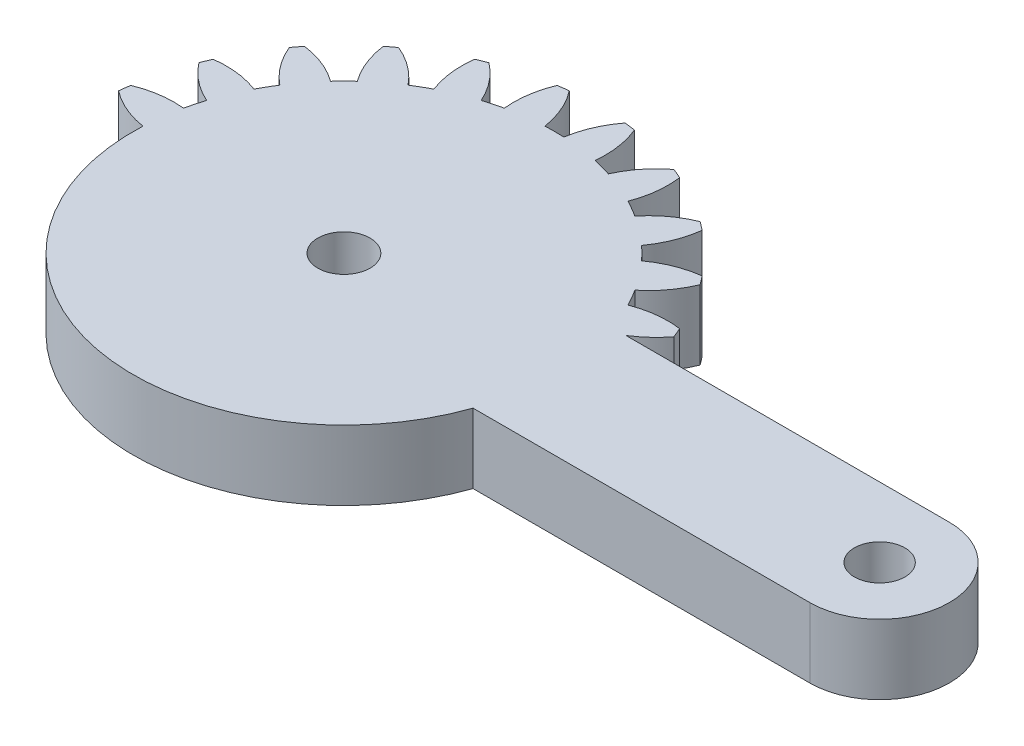
SolidWorks part; units mm, degrees
ref_plane "Front Plane" through (0, 0, 0) normal (0, 0, 1) x (1, 0, 0)
ref_plane "Top Plane" through (0, 0, 0) normal (0, 1, 0) x (1, 0, 0)
ref_plane "Right Plane" through (0, 0, 0) normal (1, 0, 0) x (0, 0, -1)
sketch "Sketch1" plane through (0, 0, 0) normal (0, 1, 0) x (1, 0, 0)
  line L0 (20.6437, 4) -> (2.0816, 4)
  line L1 (2.0816, -4) -> (20.6437, -4)
  arc A0 (2.0816, 4) -> (3.5217, 5.3071) centre (-0.7683, 8.5867) ccw
  arc A1 (3.5217, 5.3071) -> (3.2829, 5.8838) centre (-10.1063, 0) ccw
  arc A2 (3.2829, 5.8838) -> (0.6271, 5.5703) centre (2.5684, 0.5313) ccw
  arc A3 (0.6271, 5.5703) -> (0.0844, 6.5103) centre (-10.1063, 0) ccw
  arc A4 (0.0844, 6.5103) -> (1.6838, 8.6535) centre (-3.3089, 10.711) ccw
  arc A5 (1.6838, 8.6535) -> (1.3038, 9.1487) centre (-10.1063, 0) ccw
  arc A6 (1.3038, 9.1487) -> (-1.1803, 8.1585) centre (1.999, 3.7936) ccw
  arc A7 (-1.1803, 8.1585) -> (-1.9479, 8.926) centre (-10.1063, 0) ccw
  arc A8 (-1.9479, 8.926) -> (-0.9576, 11.4102) centre (-6.3127, 12.1053) ccw
  arc A9 (-0.9576, 11.4102) -> (-1.4528, 11.7901) centre (-10.1063, 0) ccw
  arc A10 (-1.4528, 11.7901) -> (-3.596, 10.1907) centre (0.6046, 6.7975) ccw
  arc A11 (-3.596, 10.1907) -> (-4.5361, 10.7334) centre (-10.1063, 0) ccw
  arc A12 (-4.5361, 10.7334) -> (-4.2225, 13.3892) centre (-9.5751, 12.6747) ccw
  arc A13 (-4.2225, 13.3892) -> (-4.7992, 13.6281) centre (-10.1063, 0) ccw
  arc A14 (-4.7992, 13.6281) -> (-6.4554, 11.5285) centre (-1.5196, 9.3381) ccw
  arc A15 (-6.4554, 11.5285) -> (-7.5039, 11.8094) centre (-10.1063, 0) ccw
  arc A16 (-7.5039, 11.8094) -> (-7.8884, 14.4558) centre (-12.8736, 12.3803) ccw
  arc A17 (-7.8884, 14.4558) -> (-8.5072, 14.5373) centre (-10.1063, 0) ccw
  arc A18 (-8.5072, 14.5373) -> (-9.5636, 12.0806) centre (-4.2291, 11.2423) ccw
  arc A19 (-9.5636, 12.0806) -> (-10.6491, 12.0806) centre (-10.1063, 0) ccw
  arc A20 (-10.6491, 12.0806) -> (-11.7054, 14.5373) centre (-15.9836, 11.2423) ccw
  arc A21 (-11.7054, 14.5373) -> (-12.3243, 14.4558) centre (-10.1063, 0) ccw
  arc A22 (-12.3243, 14.4558) -> (-12.7088, 11.8094) centre (-7.3391, 12.3803) ccw
  arc A23 (-12.7088, 11.8094) -> (-13.7573, 11.5285) centre (-10.1063, 0) ccw
  arc A24 (-13.7573, 11.5285) -> (-15.4135, 13.6281) centre (-18.6931, 9.3381) ccw
  arc A25 (-15.4135, 13.6281) -> (-15.9901, 13.3892) centre (-10.1063, 0) ccw
  arc A26 (-15.9901, 13.3892) -> (-15.6766, 10.7334) centre (-10.6376, 12.6747) ccw
  arc A27 (-15.6766, 10.7334) -> (-16.6166, 10.1907) centre (-10.1063, 0) ccw
  arc A28 (-16.6166, 10.1907) -> (-18.7599, 11.7901) centre (-20.8173, 6.7975) ccw
  arc A29 (-18.7599, 11.7901) -> (-19.255, 11.4102) centre (-10.1063, 0) ccw
  arc A30 (-19.255, 11.4102) -> (-18.2648, 8.926) centre (-13.9, 12.1053) ccw
  arc A31 (-18.2648, 8.926) -> (-19.0324, 8.1585) centre (-10.1063, 0) ccw
  arc A32 (-19.0324, 8.1585) -> (-21.5165, 9.1487) centre (-22.2117, 3.7936) ccw
  arc A33 (-21.5165, 9.1487) -> (-21.8965, 8.6535) centre (-10.1063, 0) ccw
  arc A34 (-21.8965, 8.6535) -> (-20.2971, 6.5103) centre (-16.9038, 10.711) ccw
  arc A35 (-20.2971, 6.5103) -> (-20.8398, 5.5703) centre (-10.1063, 0) ccw
  arc A36 (-20.8398, 5.5703) -> (-23.4956, 5.8838) centre (-22.7811, 0.5313) ccw
  arc A37 (-23.4956, 5.8838) -> (-23.7344, 5.3071) centre (-10.1063, 0) ccw
  arc A38 (-23.7344, 5.3071) -> (-21.6348, 3.6509) centre (-19.4444, 8.5867) ccw
  arc A39 (-21.6348, 3.6509) -> (-21.9157, 2.6025) centre (-10.1063, 0) ccw
  arc A40 (-21.9157, 2.6025) -> (-24.5622, 2.2179) centre (-22.4867, -2.7673) ccw
  arc A41 (-24.5622, 2.2179) -> (-24.6437, 1.5991) centre (-10.1063, 0) ccw
  arc A42 (-24.6437, 1.5991) -> (-22.1869, 0.5427) centre (-21.3486, 5.8773) ccw
  arc A43 (-22.1869, 0.5427) -> (-22.1869, -0.5427) centre (-10.1063, 0) ccw
  arc A44 (-22.1869, -0.5427) -> (-24.6437, -1.5991) centre (-21.3486, -5.8773) ccw
  arc A45 (-24.6437, -1.5991) -> (-24.5622, -2.2179) centre (-10.1063, 0) ccw
  arc A46 (-24.5622, -2.2179) -> (-21.9157, -2.6025) centre (-22.4867, 2.7673) ccw
  arc A47 (-21.9157, -2.6025) -> (-21.6348, -3.6509) centre (-10.1063, 0) ccw
  arc A48 (-21.6348, -3.6509) -> (-23.7344, -5.3071) centre (-19.4444, -8.5867) ccw
  arc A49 (-23.7344, -5.3071) -> (-23.4956, -5.8838) centre (-10.1063, 0) ccw
  arc A50 (-23.4956, -5.8838) -> (-20.8398, -5.5703) centre (-22.7811, -0.5313) ccw
  arc A51 (-20.8398, -5.5703) -> (-20.2971, -6.5103) centre (-10.1063, 0) ccw
  arc A52 (-20.2971, -6.5103) -> (-21.8965, -8.6535) centre (-16.9038, -10.711) ccw
  arc A53 (-21.8965, -8.6535) -> (-21.5165, -9.1487) centre (-10.1063, 0) ccw
  arc A54 (-21.5165, -9.1487) -> (-19.0324, -8.1585) centre (-22.2117, -3.7936) ccw
  arc A55 (-19.0324, -8.1585) -> (-18.2648, -8.926) centre (-10.1063, 0) ccw
  arc A56 (-18.2648, -8.926) -> (-19.255, -11.4102) centre (-13.9, -12.1053) ccw
  arc A57 (-19.255, -11.4102) -> (-18.7599, -11.7901) centre (-10.1063, 0) ccw
  arc A58 (-18.7599, -11.7901) -> (-16.6166, -10.1907) centre (-20.8173, -6.7975) ccw
  arc A59 (-16.6166, -10.1907) -> (-15.6766, -10.7334) centre (-10.1063, 0) ccw
  arc A60 (-15.6766, -10.7334) -> (-15.9901, -13.3892) centre (-10.6376, -12.6747) ccw
  arc A61 (-15.9901, -13.3892) -> (-15.4135, -13.6281) centre (-10.1063, 0) ccw
  arc A62 (-15.4135, -13.6281) -> (-13.7573, -11.5285) centre (-18.6931, -9.3381) ccw
  arc A63 (-13.7573, -11.5285) -> (-12.7088, -11.8094) centre (-10.1063, 0) ccw
  arc A64 (-12.7088, -11.8094) -> (-12.3243, -14.4558) centre (-7.3391, -12.3803) ccw
  arc A65 (-12.3243, -14.4558) -> (-11.7054, -14.5373) centre (-10.1063, 0) ccw
  arc A66 (-11.7054, -14.5373) -> (-10.6491, -12.0806) centre (-15.9836, -11.2423) ccw
  arc A67 (-10.6491, -12.0806) -> (-9.5636, -12.0806) centre (-10.1063, 0) ccw
  arc A68 (-9.5636, -12.0806) -> (-8.5072, -14.5373) centre (-4.2291, -11.2423) ccw
  arc A69 (-8.5072, -14.5373) -> (-7.8884, -14.4558) centre (-10.1063, 0) ccw
  arc A70 (-7.8884, -14.4558) -> (-7.5039, -11.8094) centre (-12.8736, -12.3803) ccw
  arc A71 (-7.5039, -11.8094) -> (-6.4554, -11.5285) centre (-10.1063, 0) ccw
  arc A72 (-6.4554, -11.5285) -> (-4.7992, -13.6281) centre (-1.5196, -9.3381) ccw
  arc A73 (-4.7992, -13.6281) -> (-4.2225, -13.3892) centre (-10.1063, 0) ccw
  arc A74 (-4.2225, -13.3892) -> (-4.5361, -10.7334) centre (-9.5751, -12.6747) ccw
  arc A75 (-4.5361, -10.7334) -> (-3.596, -10.1907) centre (-10.1063, 0) ccw
  arc A76 (-3.596, -10.1907) -> (-1.4528, -11.7901) centre (0.6046, -6.7975) ccw
  arc A77 (-1.4528, -11.7901) -> (-0.9576, -11.4102) centre (-10.1063, 0) ccw
  arc A78 (-0.9576, -11.4102) -> (-1.9479, -8.926) centre (-6.3127, -12.1053) ccw
  arc A79 (-1.9479, -8.926) -> (-1.1803, -8.1585) centre (-10.1063, 0) ccw
  arc A80 (-1.1803, -8.1585) -> (1.3038, -9.1487) centre (1.999, -3.7936) ccw
  arc A81 (1.3038, -9.1487) -> (1.6838, -8.6535) centre (-10.1063, 0) ccw
  arc A82 (1.6838, -8.6535) -> (0.0844, -6.5103) centre (-3.3089, -10.711) ccw
  arc A83 (0.0844, -6.5103) -> (0.6271, -5.5703) centre (-10.1063, 0) ccw
  arc A84 (0.6271, -5.5703) -> (3.2829, -5.8838) centre (2.5684, -0.5313) ccw
  arc A85 (3.2829, -5.8838) -> (3.5217, -5.3071) centre (-10.1063, 0) ccw
  arc A86 (3.5217, -5.3071) -> (2.0816, -4) centre (-0.7683, -8.5867) ccw
  arc A87 (20.6437, -4) -> (20.6437, 4) centre (20.6437, 0) ccw
  circle A88 centre (-10.1063, 0) radius 1.5
  circle A89 centre (20.6437, 0) radius 1.45
  dimension "D1" = 3
  dimension "D2" = 2.9
extrude "Boss-Extrude1" add sketch "Sketch1" along normal blind 4
sketch "Sketch2" plane through (0, 4, 0) normal (0, 1, 0) x (1, 0, 0)
  line L0 (2.0816, -4) -> (1.3057, -4)
  line L2 (20.6437, 4) -> (2.0816, 4)
  line L3 (2.0816, -4) -> (20.6437, -4)
  line L4 (20.6437, 4) -> (2.0816, 4)
  line L5 (2.0816, -4) -> (20.6437, -4)
  circle A0 centre (-10.1063, 0) radius 12.0927
  arc A88 (20.6437, -4) -> (20.6437, 4) centre (20.6437, 0) ccw
  arc A89 (2.0816, 4) -> (3.5217, 5.3071) centre (-0.7683, 8.5867) ccw
  arc A90 (3.5217, 5.3071) -> (3.2829, 5.8838) centre (-10.1063, 0) ccw
  arc A91 (3.2829, 5.8838) -> (0.6271, 5.5703) centre (2.5684, 0.5313) ccw
  arc A92 (0.6271, 5.5703) -> (0.0844, 6.5103) centre (-10.1063, 0) ccw
  arc A93 (0.0844, 6.5103) -> (1.6838, 8.6535) centre (-3.3089, 10.711) ccw
  arc A94 (1.6838, 8.6535) -> (1.3038, 9.1487) centre (-10.1063, 0) ccw
  arc A95 (1.3038, 9.1487) -> (-1.1803, 8.1585) centre (1.999, 3.7936) ccw
  arc A96 (-1.1803, 8.1585) -> (-1.9479, 8.926) centre (-10.1063, 0) ccw
  arc A97 (-1.9479, 8.926) -> (-0.9576, 11.4102) centre (-6.3127, 12.1053) ccw
  arc A98 (-0.9576, 11.4102) -> (-1.4528, 11.7901) centre (-10.1063, 0) ccw
  arc A99 (-1.4528, 11.7901) -> (-3.596, 10.1907) centre (0.6046, 6.7975) ccw
  arc A100 (-3.596, 10.1907) -> (-4.5361, 10.7334) centre (-10.1063, 0) ccw
  arc A101 (-4.5361, 10.7334) -> (-4.2225, 13.3892) centre (-9.5751, 12.6747) ccw
  arc A102 (-4.2225, 13.3892) -> (-4.7992, 13.6281) centre (-10.1063, 0) ccw
  arc A103 (-4.7992, 13.6281) -> (-6.4554, 11.5285) centre (-1.5196, 9.3381) ccw
  arc A104 (-6.4554, 11.5285) -> (-7.5039, 11.8094) centre (-10.1063, 0) ccw
  arc A105 (-7.5039, 11.8094) -> (-7.8884, 14.4558) centre (-12.8736, 12.3803) ccw
  arc A106 (-7.8884, 14.4558) -> (-8.5072, 14.5373) centre (-10.1063, 0) ccw
  arc A107 (-8.5072, 14.5373) -> (-9.5636, 12.0806) centre (-4.2291, 11.2423) ccw
  arc A108 (-9.5636, 12.0806) -> (-10.6491, 12.0806) centre (-10.1063, 0) ccw
  arc A109 (-10.6491, 12.0806) -> (-11.7054, 14.5373) centre (-15.9836, 11.2423) ccw
  arc A110 (-11.7054, 14.5373) -> (-12.3243, 14.4558) centre (-10.1063, 0) ccw
  arc A111 (-12.3243, 14.4558) -> (-12.7088, 11.8094) centre (-7.3391, 12.3803) ccw
  arc A112 (-12.7088, 11.8094) -> (-13.7573, 11.5285) centre (-10.1063, 0) ccw
  arc A113 (-13.7573, 11.5285) -> (-15.4135, 13.6281) centre (-18.6931, 9.3381) ccw
  arc A114 (-15.4135, 13.6281) -> (-15.9901, 13.3892) centre (-10.1063, 0) ccw
  arc A115 (-15.9901, 13.3892) -> (-15.6766, 10.7334) centre (-10.6376, 12.6747) ccw
  arc A116 (-15.6766, 10.7334) -> (-16.6166, 10.1907) centre (-10.1063, 0) ccw
  arc A117 (-16.6166, 10.1907) -> (-18.7599, 11.7901) centre (-20.8173, 6.7975) ccw
  arc A118 (-18.7599, 11.7901) -> (-19.255, 11.4102) centre (-10.1063, 0) ccw
  arc A119 (-19.255, 11.4102) -> (-18.2648, 8.926) centre (-13.9, 12.1053) ccw
  arc A120 (-18.2648, 8.926) -> (-19.0324, 8.1585) centre (-10.1063, 0) ccw
  arc A121 (-19.0324, 8.1585) -> (-21.5165, 9.1487) centre (-22.2117, 3.7936) ccw
  arc A122 (-21.5165, 9.1487) -> (-21.8965, 8.6535) centre (-10.1063, 0) ccw
  arc A123 (-21.8965, 8.6535) -> (-20.2971, 6.5103) centre (-16.9038, 10.711) ccw
  arc A124 (-20.2971, 6.5103) -> (-20.8398, 5.5703) centre (-10.1063, 0) ccw
  arc A125 (-20.8398, 5.5703) -> (-23.4956, 5.8838) centre (-22.7811, 0.5313) ccw
  arc A126 (-23.4956, 5.8838) -> (-23.7344, 5.3071) centre (-10.1063, 0) ccw
  arc A127 (-23.7344, 5.3071) -> (-21.6348, 3.6509) centre (-19.4444, 8.5867) ccw
  arc A128 (-21.6348, 3.6509) -> (-21.9157, 2.6025) centre (-10.1063, 0) ccw
  arc A129 (-21.9157, 2.6025) -> (-24.5622, 2.2179) centre (-22.4867, -2.7673) ccw
  arc A130 (-24.5622, 2.2179) -> (-24.6437, 1.5991) centre (-10.1063, 0) ccw
  arc A131 (-24.6437, 1.5991) -> (-22.1869, 0.5427) centre (-21.3486, 5.8773) ccw
  arc A132 (-22.1869, 0.5427) -> (-22.1869, -0.5427) centre (-10.1063, 0) ccw
  arc A133 (-22.1869, -0.5427) -> (-24.6437, -1.5991) centre (-21.3486, -5.8773) ccw
  arc A134 (-24.6437, -1.5991) -> (-24.5622, -2.2179) centre (-10.1063, 0) ccw
  arc A135 (-24.5622, -2.2179) -> (-21.9157, -2.6025) centre (-22.4867, 2.7673) ccw
  arc A136 (-21.9157, -2.6025) -> (-21.6348, -3.6509) centre (-10.1063, 0) ccw
  arc A137 (-21.6348, -3.6509) -> (-23.7344, -5.3071) centre (-19.4444, -8.5867) ccw
  arc A138 (-23.7344, -5.3071) -> (-23.4956, -5.8838) centre (-10.1063, 0) ccw
  arc A139 (-23.4956, -5.8838) -> (-20.8398, -5.5703) centre (-22.7811, -0.5313) ccw
  arc A140 (-20.8398, -5.5703) -> (-20.2971, -6.5103) centre (-10.1063, 0) ccw
  arc A141 (-20.2971, -6.5103) -> (-21.8965, -8.6535) centre (-16.9038, -10.711) ccw
  arc A142 (-21.8965, -8.6535) -> (-21.5165, -9.1487) centre (-10.1063, 0) ccw
  arc A143 (-21.5165, -9.1487) -> (-19.0324, -8.1585) centre (-22.2117, -3.7936) ccw
  arc A144 (-19.0324, -8.1585) -> (-18.2648, -8.926) centre (-10.1063, 0) ccw
  arc A145 (-18.2648, -8.926) -> (-19.255, -11.4102) centre (-13.9, -12.1053) ccw
  arc A146 (-19.255, -11.4102) -> (-18.7599, -11.7901) centre (-10.1063, 0) ccw
  arc A147 (-18.7599, -11.7901) -> (-16.6166, -10.1907) centre (-20.8173, -6.7975) ccw
  arc A148 (-16.6166, -10.1907) -> (-15.6766, -10.7334) centre (-10.1063, 0) ccw
  arc A149 (-15.6766, -10.7334) -> (-15.9901, -13.3892) centre (-10.6376, -12.6747) ccw
  arc A150 (-15.9901, -13.3892) -> (-15.4135, -13.6281) centre (-10.1063, 0) ccw
  arc A151 (-15.4135, -13.6281) -> (-13.7573, -11.5285) centre (-18.6931, -9.3381) ccw
  arc A152 (-13.7573, -11.5285) -> (-12.7088, -11.8094) centre (-10.1063, 0) ccw
  arc A153 (-12.7088, -11.8094) -> (-12.3243, -14.4558) centre (-7.3391, -12.3803) ccw
  arc A154 (-12.3243, -14.4558) -> (-11.7054, -14.5373) centre (-10.1063, 0) ccw
  arc A155 (-11.7054, -14.5373) -> (-10.6491, -12.0806) centre (-15.9836, -11.2423) ccw
  arc A156 (-10.6491, -12.0806) -> (-9.5636, -12.0806) centre (-10.1063, 0) ccw
  arc A157 (-9.5636, -12.0806) -> (-8.5072, -14.5373) centre (-4.2291, -11.2423) ccw
  arc A158 (-8.5072, -14.5373) -> (-7.8884, -14.4558) centre (-10.1063, 0) ccw
  arc A159 (-7.8884, -14.4558) -> (-7.5039, -11.8094) centre (-12.8736, -12.3803) ccw
  arc A160 (-7.5039, -11.8094) -> (-6.4554, -11.5285) centre (-10.1063, 0) ccw
  arc A161 (-6.4554, -11.5285) -> (-4.7992, -13.6281) centre (-1.5196, -9.3381) ccw
  arc A162 (-4.7992, -13.6281) -> (-4.2225, -13.3892) centre (-10.1063, 0) ccw
  arc A163 (-4.2225, -13.3892) -> (-4.5361, -10.7334) centre (-9.5751, -12.6747) ccw
  arc A164 (-4.5361, -10.7334) -> (-3.596, -10.1907) centre (-10.1063, 0) ccw
  arc A165 (-3.596, -10.1907) -> (-1.4528, -11.7901) centre (0.6046, -6.7975) ccw
  arc A166 (-1.4528, -11.7901) -> (-0.9576, -11.4102) centre (-10.1063, 0) ccw
  arc A167 (-0.9576, -11.4102) -> (-1.9479, -8.926) centre (-6.3127, -12.1053) ccw
  arc A168 (-1.9479, -8.926) -> (-1.1803, -8.1585) centre (-10.1063, 0) ccw
  arc A169 (-1.1803, -8.1585) -> (1.3038, -9.1487) centre (1.999, -3.7936) ccw
  arc A170 (1.3038, -9.1487) -> (1.6838, -8.6535) centre (-10.1063, 0) ccw
  arc A171 (1.6838, -8.6535) -> (0.0844, -6.5103) centre (-3.3089, -10.711) ccw
  arc A172 (0.0844, -6.5103) -> (0.6271, -5.5703) centre (-10.1063, 0) ccw
  arc A173 (0.6271, -5.5703) -> (3.2829, -5.8838) centre (2.5684, -0.5313) ccw
  arc A174 (3.2829, -5.8838) -> (3.5217, -5.3071) centre (-10.1063, 0) ccw
  arc A175 (3.5217, -5.3071) -> (2.0816, -4) centre (-0.7683, -8.5867) ccw
  arc A176 (20.6437, -4) -> (20.6437, 4) centre (20.6437, 0) ccw
  arc A177 (2.0816, 4) -> (3.5217, 5.3071) centre (-0.7683, 8.5867) ccw
  arc A178 (3.5217, 5.3071) -> (3.2829, 5.8838) centre (-10.1063, 0) ccw
  arc A179 (3.2829, 5.8838) -> (0.6271, 5.5703) centre (2.5684, 0.5313) ccw
  arc A180 (0.6271, 5.5703) -> (0.0844, 6.5103) centre (-10.1063, 0) ccw
  arc A181 (0.0844, 6.5103) -> (1.6838, 8.6535) centre (-3.3089, 10.711) ccw
  arc A182 (1.6838, 8.6535) -> (1.3038, 9.1487) centre (-10.1063, 0) ccw
  arc A183 (1.3038, 9.1487) -> (-1.1803, 8.1585) centre (1.999, 3.7936) ccw
  arc A184 (-1.1803, 8.1585) -> (-1.9479, 8.926) centre (-10.1063, 0) ccw
  arc A185 (-1.9479, 8.926) -> (-0.9576, 11.4102) centre (-6.3127, 12.1053) ccw
  arc A186 (-0.9576, 11.4102) -> (-1.4528, 11.7901) centre (-10.1063, 0) ccw
  arc A187 (-1.4528, 11.7901) -> (-3.596, 10.1907) centre (0.6046, 6.7975) ccw
  arc A188 (-3.596, 10.1907) -> (-4.5361, 10.7334) centre (-10.1063, 0) ccw
  arc A189 (-4.5361, 10.7334) -> (-4.2225, 13.3892) centre (-9.5751, 12.6747) ccw
  arc A190 (-4.2225, 13.3892) -> (-4.7992, 13.6281) centre (-10.1063, 0) ccw
  arc A191 (-4.7992, 13.6281) -> (-6.4554, 11.5285) centre (-1.5196, 9.3381) ccw
  arc A192 (-6.4554, 11.5285) -> (-7.5039, 11.8094) centre (-10.1063, 0) ccw
  arc A193 (-7.5039, 11.8094) -> (-7.8884, 14.4558) centre (-12.8736, 12.3803) ccw
  arc A194 (-7.8884, 14.4558) -> (-8.5072, 14.5373) centre (-10.1063, 0) ccw
  arc A195 (-8.5072, 14.5373) -> (-9.5636, 12.0806) centre (-4.2291, 11.2423) ccw
  arc A196 (-9.5636, 12.0806) -> (-10.6491, 12.0806) centre (-10.1063, 0) ccw
  arc A197 (-10.6491, 12.0806) -> (-11.7054, 14.5373) centre (-15.9836, 11.2423) ccw
  arc A198 (-11.7054, 14.5373) -> (-12.3243, 14.4558) centre (-10.1063, 0) ccw
  arc A199 (-12.3243, 14.4558) -> (-12.7088, 11.8094) centre (-7.3391, 12.3803) ccw
  arc A200 (-12.7088, 11.8094) -> (-13.7573, 11.5285) centre (-10.1063, 0) ccw
  arc A201 (-13.7573, 11.5285) -> (-15.4135, 13.6281) centre (-18.6931, 9.3381) ccw
  arc A202 (-15.4135, 13.6281) -> (-15.9901, 13.3892) centre (-10.1063, 0) ccw
  arc A203 (-15.9901, 13.3892) -> (-15.6766, 10.7334) centre (-10.6376, 12.6747) ccw
  arc A204 (-15.6766, 10.7334) -> (-16.6166, 10.1907) centre (-10.1063, 0) ccw
  arc A205 (-16.6166, 10.1907) -> (-18.7599, 11.7901) centre (-20.8173, 6.7975) ccw
  arc A206 (-18.7599, 11.7901) -> (-19.255, 11.4102) centre (-10.1063, 0) ccw
  arc A207 (-19.255, 11.4102) -> (-18.2648, 8.926) centre (-13.9, 12.1053) ccw
  arc A208 (-18.2648, 8.926) -> (-19.0324, 8.1585) centre (-10.1063, 0) ccw
  arc A209 (-19.0324, 8.1585) -> (-21.5165, 9.1487) centre (-22.2117, 3.7936) ccw
  arc A210 (-21.5165, 9.1487) -> (-21.8965, 8.6535) centre (-10.1063, 0) ccw
  arc A211 (-21.8965, 8.6535) -> (-20.2971, 6.5103) centre (-16.9038, 10.711) ccw
  arc A212 (-20.2971, 6.5103) -> (-20.8398, 5.5703) centre (-10.1063, 0) ccw
  arc A213 (-20.8398, 5.5703) -> (-23.4956, 5.8838) centre (-22.7811, 0.5313) ccw
  arc A214 (-23.4956, 5.8838) -> (-23.7344, 5.3071) centre (-10.1063, 0) ccw
  arc A215 (-23.7344, 5.3071) -> (-21.6348, 3.6509) centre (-19.4444, 8.5867) ccw
  arc A216 (-21.6348, 3.6509) -> (-21.9157, 2.6025) centre (-10.1063, 0) ccw
  arc A217 (-21.9157, 2.6025) -> (-24.5622, 2.2179) centre (-22.4867, -2.7673) ccw
  arc A218 (-24.5622, 2.2179) -> (-24.6437, 1.5991) centre (-10.1063, 0) ccw
  arc A219 (-24.6437, 1.5991) -> (-22.1869, 0.5427) centre (-21.3486, 5.8773) ccw
  arc A220 (-22.1869, 0.5427) -> (-22.1869, -0.5427) centre (-10.1063, 0) ccw
  arc A221 (-22.1869, -0.5427) -> (-24.6437, -1.5991) centre (-21.3486, -5.8773) ccw
  arc A222 (-24.6437, -1.5991) -> (-24.5622, -2.2179) centre (-10.1063, 0) ccw
  arc A223 (-24.5622, -2.2179) -> (-21.9157, -2.6025) centre (-22.4867, 2.7673) ccw
  arc A224 (-21.9157, -2.6025) -> (-21.6348, -3.6509) centre (-10.1063, 0) ccw
  arc A225 (-21.6348, -3.6509) -> (-23.7344, -5.3071) centre (-19.4444, -8.5867) ccw
  arc A226 (-23.7344, -5.3071) -> (-23.4956, -5.8838) centre (-10.1063, 0) ccw
  arc A227 (-23.4956, -5.8838) -> (-20.8398, -5.5703) centre (-22.7811, -0.5313) ccw
  arc A228 (-20.8398, -5.5703) -> (-20.2971, -6.5103) centre (-10.1063, 0) ccw
  arc A229 (-20.2971, -6.5103) -> (-21.8965, -8.6535) centre (-16.9038, -10.711) ccw
  arc A230 (-21.8965, -8.6535) -> (-21.5165, -9.1487) centre (-10.1063, 0) ccw
  arc A231 (-21.5165, -9.1487) -> (-19.0324, -8.1585) centre (-22.2117, -3.7936) ccw
  arc A232 (-19.0324, -8.1585) -> (-18.2648, -8.926) centre (-10.1063, 0) ccw
  arc A233 (-18.2648, -8.926) -> (-19.255, -11.4102) centre (-13.9, -12.1053) ccw
  arc A234 (-19.255, -11.4102) -> (-18.7599, -11.7901) centre (-10.1063, 0) ccw
  arc A235 (-18.7599, -11.7901) -> (-16.6166, -10.1907) centre (-20.8173, -6.7975) ccw
  arc A236 (-16.6166, -10.1907) -> (-15.6766, -10.7334) centre (-10.1063, 0) ccw
  arc A237 (-15.6766, -10.7334) -> (-15.9901, -13.3892) centre (-10.6376, -12.6747) ccw
  arc A238 (-15.9901, -13.3892) -> (-15.4135, -13.6281) centre (-10.1063, 0) ccw
  arc A239 (-15.4135, -13.6281) -> (-13.7573, -11.5285) centre (-18.6931, -9.3381) ccw
  arc A240 (-13.7573, -11.5285) -> (-12.7088, -11.8094) centre (-10.1063, 0) ccw
  arc A241 (-12.7088, -11.8094) -> (-12.3243, -14.4558) centre (-7.3391, -12.3803) ccw
  arc A242 (-12.3243, -14.4558) -> (-11.7054, -14.5373) centre (-10.1063, 0) ccw
  arc A243 (-11.7054, -14.5373) -> (-10.6491, -12.0806) centre (-15.9836, -11.2423) ccw
  arc A244 (-10.6491, -12.0806) -> (-9.5636, -12.0806) centre (-10.1063, 0) ccw
  arc A245 (-9.5636, -12.0806) -> (-8.5072, -14.5373) centre (-4.2291, -11.2423) ccw
  arc A246 (-8.5072, -14.5373) -> (-7.8884, -14.4558) centre (-10.1063, 0) ccw
  arc A247 (-7.8884, -14.4558) -> (-7.5039, -11.8094) centre (-12.8736, -12.3803) ccw
  arc A248 (-7.5039, -11.8094) -> (-6.4554, -11.5285) centre (-10.1063, 0) ccw
  arc A249 (-6.4554, -11.5285) -> (-4.7992, -13.6281) centre (-1.5196, -9.3381) ccw
  arc A250 (-4.7992, -13.6281) -> (-4.2225, -13.3892) centre (-10.1063, 0) ccw
  arc A251 (-4.2225, -13.3892) -> (-4.5361, -10.7334) centre (-9.5751, -12.6747) ccw
  arc A252 (-4.5361, -10.7334) -> (-3.596, -10.1907) centre (-10.1063, 0) ccw
  arc A253 (-3.596, -10.1907) -> (-1.4528, -11.7901) centre (0.6046, -6.7975) ccw
  arc A254 (-1.4528, -11.7901) -> (-0.9576, -11.4102) centre (-10.1063, 0) ccw
  arc A255 (-0.9576, -11.4102) -> (-1.9479, -8.926) centre (-6.3127, -12.1053) ccw
  arc A256 (-1.9479, -8.926) -> (-1.1803, -8.1585) centre (-10.1063, 0) ccw
  arc A257 (-1.1803, -8.1585) -> (1.3038, -9.1487) centre (1.999, -3.7936) ccw
  arc A258 (1.3038, -9.1487) -> (1.6838, -8.6535) centre (-10.1063, 0) ccw
  arc A259 (1.6838, -8.6535) -> (0.0844, -6.5103) centre (-3.3089, -10.711) ccw
  arc A260 (0.0844, -6.5103) -> (0.6271, -5.5703) centre (-10.1063, 0) ccw
  arc A261 (0.6271, -5.5703) -> (3.2829, -5.8838) centre (2.5684, -0.5313) ccw
  arc A262 (3.2829, -5.8838) -> (3.5217, -5.3071) centre (-10.1063, 0) ccw
  arc A263 (3.5217, -5.3071) -> (2.0816, -4) centre (-0.7683, -8.5867) ccw
  dimension "D1" = 0
extrude "Cut-Extrude1" cut sketch "Sketch2" against normal blind 10 contours A222 A223 A0 A221 | A226 A227 A0 A225 | A230 A231 A0 A229 | A234 A235 A0 A233 | A238 A239 A0 A237 | A242 A243 A0 A241 | A246 A247 A0 A245 | A250 A251 A0 A249 | A254 A255 A0 A253 | A258 A259 A0 A257 | A262 A263 L0 A0 A261
